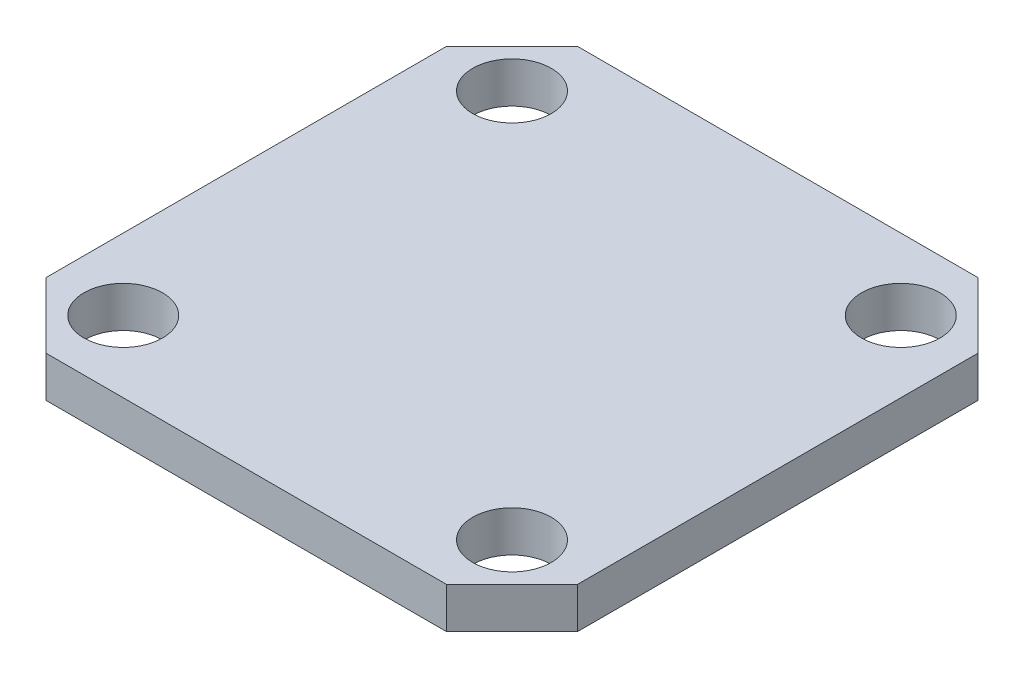
SolidWorks part; units mm, degrees
material "6061-T6 (SS)"
ref_plane "Front Plane" through (0, 0, 0) normal (0, 0, 1) x (1, 0, 0)
ref_plane "Top Plane" through (0, 0, 0) normal (0, 1, 0) x (1, 0, 0)
ref_plane "Right Plane" through (0, 0, 0) normal (1, 0, 0) x (0, 0, -1)
sketch "Sketch1" plane through (0, 0, 0) normal (0, 1, 0) x (1, 0, 0)
  line L1 (-10.3124, 10.3124) -> (10.3124, 10.3124)
  line L2 (-10.3124, 10.3124) -> (-10.3124, -10.3124)
  line L3 (-10.3124, -10.3124) -> (10.3124, -10.3124)
  line L4 (10.3124, 10.3124) -> (10.3124, -10.3124)
  line L5 (-10.3124, 10.3124) -> (10.3124, -10.3124) construction
  line L6 (-10.3124, -10.3124) -> (10.3124, 10.3124) construction
  point P0 (0, 0)
  dimension "D1" = 20.6248
extrude "Boss-Extrude1" add sketch "Sketch1" along normal blind 1.5875
chamfer "Chamfer1" distance 2.54 angle 45 4 edges at (-10.3124, 0.7937, -10.3124) (10.3124, 0.7937, -10.3124) (10.3124, 0.7937, 10.3124) (-10.3124, 0.7937, 10.3124)
sketch "Sketch2" plane through (0, 1.5875, 0) normal (0, 1, 0) x (1, 0, 0)
  line L1 (-7.5438, 7.5438) -> (7.5438, 7.5438) construction
  line L2 (-7.5438, 7.5438) -> (-7.5438, -7.5438) construction
  line L3 (-7.5438, -7.5438) -> (7.5438, -7.5438) construction
  line L4 (7.5438, 7.5438) -> (7.5438, -7.5438) construction
  line L5 (-7.5438, 7.5438) -> (7.5438, -7.5438) construction
  line L6 (-7.5438, -7.5438) -> (7.5438, 7.5438) construction
  circle A0 centre (-7.5438, 7.5438) radius 1.524
  circle A1 centre (7.5438, 7.5438) radius 1.524
  circle A2 centre (7.5438, -7.5438) radius 1.524
  circle A3 centre (-7.5438, -7.5438) radius 1.524
  point P0 (0, 0)
  dimension "D2" = 3.048
  dimension "D1" = 15.0876
extrude "Cut-Extrude1" cut sketch "Sketch2" against normal through all
sketch "Sketch3" plane through (0, 1.5875, 0) normal (0, 1, 0) x (1, 0, 0)
  circle A0 centre (0, 0) radius 6.0071
  dimension "D1" = 12.0142
extrude "Boss-Extrude2" [suppressed] add sketch "Sketch3" along normal blind 10.9474
sketch "Sketch4" [suppressed] plane through (0, 0, 0) normal (0, -1, 0) x (1, 0, 0)
  circle A0 centre (0, 0) radius 5.7023
  dimension "D1" = 11.4046
extrude "Boss-Extrude3" [suppressed] add sketch "Sketch4" along normal blind 8.4328
